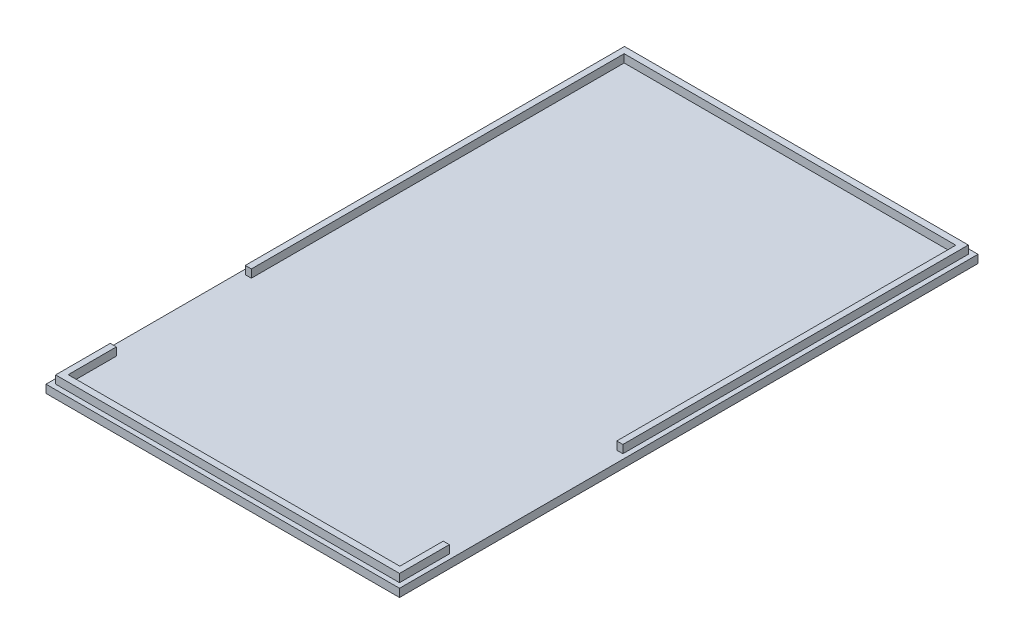
SolidWorks part; units mm, degrees
ref_plane "Front Plane" through (0, 0, 0) normal (0, 0, 1) x (1, 0, 0)
ref_plane "Top Plane" through (0, 0, 0) normal (0, 1, 0) x (1, 0, 0)
ref_plane "Right Plane" through (0, 0, 0) normal (1, 0, 0) x (0, 0, -1)
sketch "Sketch1" plane through (0, 0, 0) normal (0, 1, 0) x (1, 0, 0)
  line L1 (55, -90) -> (-55, -90)
  line L2 (55, -90) -> (55, 90)
  line L3 (55, 90) -> (-55, 90)
  line L4 (-55, -90) -> (-55, 90)
  line L5 (55, -90) -> (-55, 90) construction
  line L6 (55, 90) -> (-55, -90) construction
  point P0 (0, 0)
  dimension "D1" = 180
  dimension "D2" = 110
extrude "Boss-Extrude1" add sketch "Sketch1" along normal mid plane 2.5
sketch "Sketch2" plane through (0, 1.25, 0) normal (0, 1, 0) x (1, 0, 0)
  line L0 (55, 90) -> (-55, 90) construction
  line L1 (53.5, -88.5) -> (-53.5, -88.5)
  line L2 (53.5, -88.5) -> (53.5, -73)
  line L3 (53.5, 88.5) -> (-53.5, 88.5)
  line L4 (-53.5, -88.5) -> (-53.5, -71.5)
  line L5 (55, -90) -> (55, 90) construction
  line L6 (-55, -90) -> (55, -90) construction
  line L7 (51.6, -86.5) -> (-51.6, -86.5)
  line L8 (51.6, -86.5) -> (51.6, -73)
  line L9 (51.6, 86.5) -> (-51.6, 86.5)
  line L10 (-51.6, -86.5) -> (-51.6, -71.5)
  line L11 (-51.6, -71.5) -> (-53.5, -71.5)
  line L12 (-51.6, -29.5) -> (-53.5, -29.5)
  line L13 (-55, 90) -> (-55, -90) construction
  line L14 (-51.6, 85.1916) -> (-53.5, 88.5) construction
  line L15 (-51.6, -85.1916) -> (-53.5, -88.5) construction
  line L16 (-51.6, -29.5) -> (-51.6, 86.5)
  line L17 (-53.5, -29.5) -> (-53.5, 88.5)
  line L18 (51.6, -19) -> (53.5, -19)
  line L19 (51.6, -73) -> (53.5, -73)
  line L20 (51.6, -19) -> (51.6, 86.5)
  line L21 (53.5, -19) -> (53.5, 88.5)
  point P0 (0, 0)
  point P6 (0, 0)
  dimension "D1" = 1.5
  dimension "D2" = 1.5
  dimension "D3" = 2
  dimension "D4" = 1.9
  dimension "D5" = 1.9
  dimension "D6" = 2
  dimension "D7" = 1.5
  dimension "D8" = 1.5
  dimension "D9" = 18.5
  dimension "D10" = 60.5
  dimension "D11" = 54
  dimension "D12" = 15.5
extrude "Boss-Extrude3" add sketch "Sketch2" along normal blind 2.5
